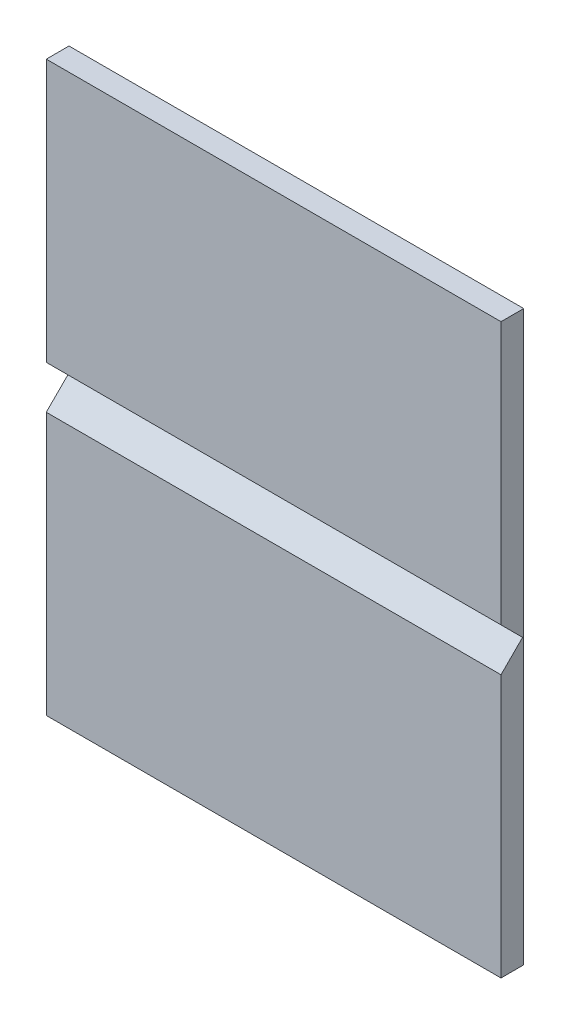
SolidWorks part; units mm, degrees
ref_plane "Front Plane" through (0, 0, 0) normal (0, 0, 1) x (1, 0, 0)
ref_plane "Top Plane" through (0, 0, 0) normal (0, 1, 0) x (1, 0, 0)
ref_plane "Right Plane" through (0, 0, 0) normal (1, 0, 0) x (0, 0, -1)
sketch "Sketch1" plane through (0, 0, 0) normal (0, 0, 1) x (1, 0, 0)
  line L1 (-200, -250) -> (200, -250)
  line L2 (-200, -250) -> (-200, 250)
  line L3 (-200, 250) -> (200, 250)
  line L4 (200, -250) -> (200, 250)
  line L5 (-200, -250) -> (200, 250) construction
  line L6 (-200, 250) -> (200, -250) construction
  point P0 (0, 0)
  dimension "D1" = 400
  dimension "D2" = 500
extrude "Boss-Extrude1" add sketch "Sketch1" along normal blind 20
sketch "Sketch2" plane through (200, 0, 0) normal (1, 0, 0) x (0, 0, -1)
  line L2 (-1, 0) -> (-20.6572, 19.6572)
  line L3 (-1, 0) -> (-20.6572, -19.6572)
  line L4 (-20.6572, -19.6572) -> (-20.6572, 19.6572)
  point P6 (0, 0)
  point P9 (0, 0)
extrude "Cut-Extrude2" cut sketch "Sketch2" against normal through all
